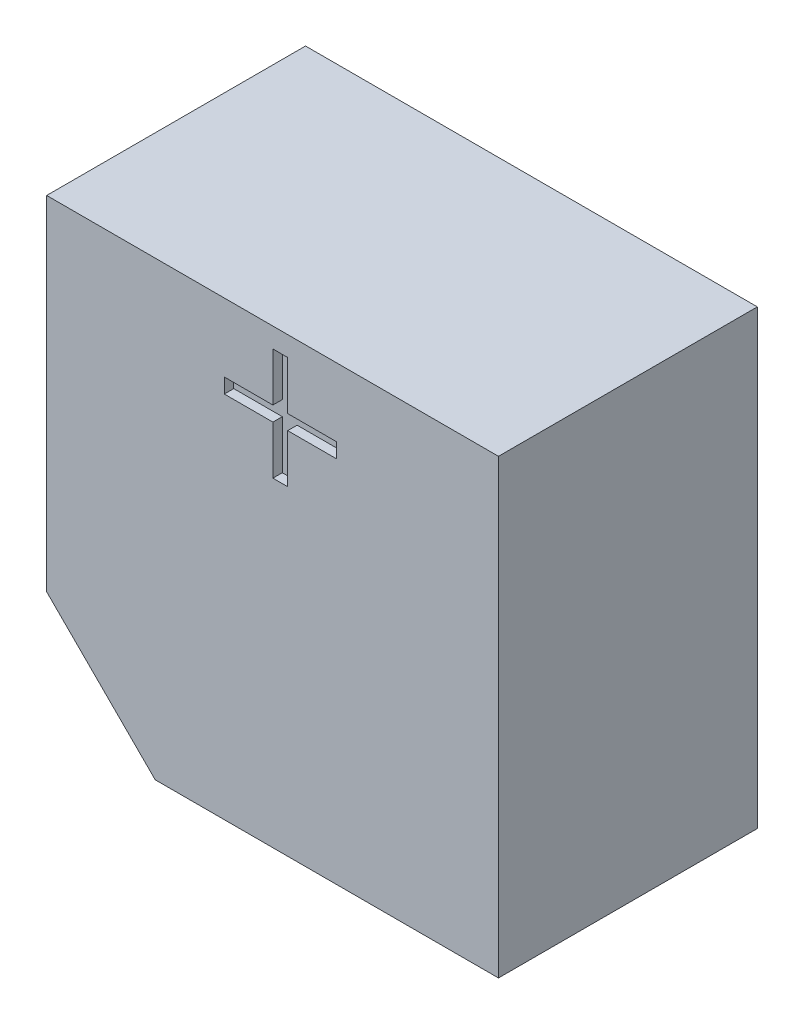
SolidWorks part; units mm, degrees
ref_plane "Plan de face" through (0, 0, 0) normal (0, 0, 1) x (1, 0, 0)
ref_plane "Plan de dessus" through (0, 0, 0) normal (0, 1, 0) x (1, 0, 0)
ref_plane "Plan de droite" through (0, 0, 0) normal (1, 0, 0) x (0, 0, -1)
sketch "Esquisse2" plane through (0, 0, 0) normal (0, 0, 1) x (1, 0, 0)
  line L1 (0, 0) -> (9.6, 0)
  line L2 (0, 0) -> (0, 9.6)
  line L3 (0, 9.6) -> (9.6, 9.6)
  line L4 (9.6, 0) -> (9.6, 9.6)
  dimension "D1" = 9.6
  dimension "D2" = 9.6
sketch "Esquisse3" plane through (0, 0, 0) normal (0, 0, 1) x (1, 0, 0)
  line L0 (0, 9.6) -> (9.6, 9.6)
  line L1 (9.6, 9.6) -> (9.6, 0)
  line L2 (9.6, 0) -> (2.3064, 0)
  line L3 (0, 0) -> (9.6, 0) construction
  line L4 (2.3064, 0) -> (0, 2.3064)
  line L5 (0, 0) -> (0, 9.6) construction
  line L6 (0, 2.3064) -> (0, 9.6)
extrude "Boss.-Extru.1" add sketch "Esquisse3" along normal blind 5.5
sketch "Esquisse4" plane through (0, 0, 5.5) normal (0, 0, 1) x (1, 0, 0)
  text T0 "+"
extrude "Enlèv. mat.-Extru.1" cut sketch "Esquisse4" against normal blind 0.2
